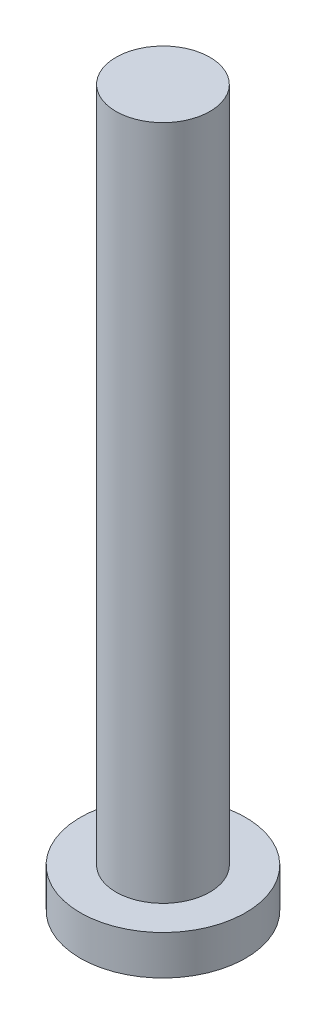
SolidWorks part; units mm, degrees
ref_plane "Front Plane" through (0, 0, 0) normal (0, 0, 1) x (1, 0, 0)
ref_plane "Top Plane" through (0, 0, 0) normal (0, 1, 0) x (1, 0, 0)
ref_plane "Right Plane" through (0, 0, 0) normal (1, 0, 0) x (0, 0, -1)
sketch "Sketch1" plane through (0, 0, 0) normal (0, 1, 0) x (1, 0, 0)
  circle A0 centre (0, 0) radius 4.4
  circle A1 centre (0, 0) radius 2.5
  dimension "D1" = 5
  dimension "D2" = 8.8
extrude "Boss-Extrude1" add sketch "Sketch1" along normal blind 2.1 contours A1 | A0 A1
sketch "Sketch2" plane through (0, 0, 0) normal (0, -1, 0) x (1, 0, 0)
  line L1 (2.8868, 0) -> (1.4434, 2.5)
  line L2 (1.4434, 2.5) -> (-1.4434, 2.5)
  line L3 (-1.4434, 2.5) -> (-2.8868, 0)
  line L4 (-2.8868, 0) -> (-1.4434, -2.5)
  line L5 (-1.4434, -2.5) -> (1.4434, -2.5)
  line L6 (1.4434, -2.5) -> (2.8868, 0)
  circle A0 centre (0, 0) radius 2.5 construction
  point P1 (0, 0)
  dimension "D1" = 5
extrude "Cut-Extrude1" cut sketch "Sketch2" against normal blind 1.27
sketch "Sketch3" plane through (0, 2.1, 0) normal (0, 1, 0) x (1, 0, 0)
  circle A1 centre (0, 0) radius 2.5
  circle A2 centre (0, 0) radius 2.5
  circle A3 centre (0, 0) radius 4.4
  circle A4 centre (0, 0) radius 4.4
  dimension "D1" = 0
  dimension "D2" = 0
extrude "Boss-Extrude2" add sketch "Sketch3" along normal blind 36 contours A2
cosmetic thread "Cosmetic Thread1" parameters "D2"=3.5662
